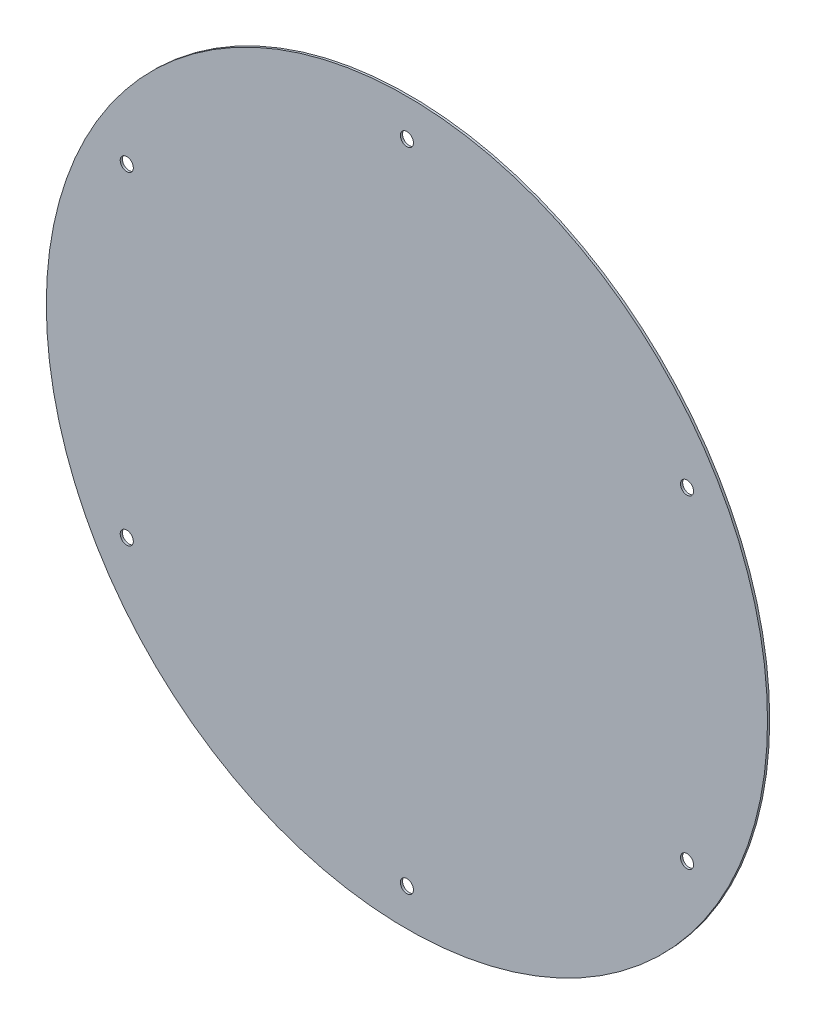
SolidWorks part; units mm, degrees
ref_plane "Front Plane" through (0, 0, 0) normal (0, 0, 1) x (1, 0, 0)
ref_plane "Top Plane" through (0, 0, 0) normal (0, 1, 0) x (1, 0, 0)
ref_plane "Right Plane" through (0, 0, 0) normal (1, 0, 0) x (0, 0, -1)
sketch "Sketch1" plane through (0, 0, 0) normal (0, 0, 1) x (1, 0, 0)
  line L0 (0, 0) -> (64.0859, 37) construction
  line L1 (0, 0) -> (0, 74) construction
  circle A0 centre (0, 0) radius 82.5
  circle A1 centre (0, 0) radius 74 construction
  circle A2 centre (0, 74) radius 1.5
  circle A3 centre (0, -74) radius 1.5
  circle A4 centre (64.0859, 37) radius 1.5
  circle A5 centre (64.0859, -37) radius 1.5
  circle A6 centre (-64.0859, -37) radius 1.5
  circle A7 centre (-64.0859, 37) radius 1.5
  dimension "D1" = 165
  dimension "D3" = 3
  dimension "D4" = 148
  dimension "D2" = 60
extrude "Boss-Extrude1" add sketch "Sketch1" along normal blind 0.5
